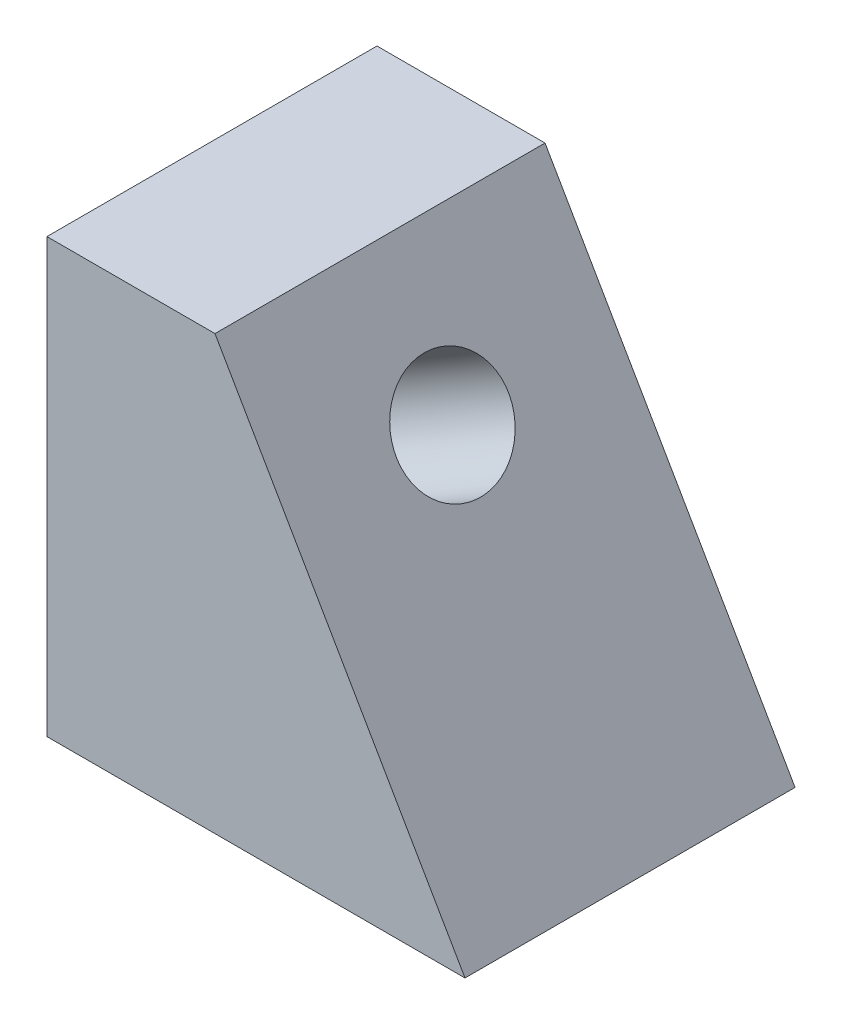
SolidWorks part; units mm, degrees
ref_plane "Front Plane" through (0, 0, 0) normal (0, 0, 1) x (1, 0, 0)
ref_plane "Top Plane" through (0, 0, 0) normal (0, 1, 0) x (1, 0, 0)
ref_plane "Right Plane" through (0, 0, 0) normal (1, 0, 0) x (0, 0, -1)
sketch "Sketch1" plane through (0, 0, 0) normal (0, 0, 1) x (1, 0, 0)
  line L1 (0, 0) -> (63.3351, 0)
  line L2 (0, 0) -> (0, 65.6066)
  line L3 (0, 65.6066) -> (63.3351, 65.6066)
  line L4 (63.3351, 0) -> (63.3351, 65.6066)
extrude "Boss-Extrude1" add sketch "Sketch1" along normal blind 50 contours L3 L4 L1 L2
sketch "Sketch2" plane through (0, 0, 50) normal (0, 0, 1) x (1, 0, 0)
  line L0 (63.3351, 0) -> (25.4571, 65.6066) construction
  line L1 (0, 65.6066) -> (63.3351, 65.6066) construction
  line L2 (0, 0) -> (63.3351, 0) construction
  line L3 (25.4571, 65.6066) -> (63.3351, 0)
  line L4 (63.3351, 0) -> (63.3351, 65.6066)
  line L5 (63.3351, 65.6066) -> (25.4571, 65.6066)
  line L6 (0, 30.3716) -> (45.8, 30.3716) construction
  line L7 (0, 0) -> (0, 65.6066) construction
  line L8 (0, 30.3716) -> (37.4018, 44.9178) construction
  dimension "D1" = 60
  dimension "D2" = 21.252
extrude "Cut-Extrude1" cut sketch "Sketch2" against normal up to surface (50 mm away) up to face at (31.6675, 32.8033, 0)
ref_plane "Plane1" through (47.5013, 27.4249, 0) normal (0.866, 0.5, 0) x (0, 0, -1)
sketch "Sketch3" plane through (47.5013, 27.4249, 0) normal (0.866, 0.5, 0) x (0, 0, -1)
  line L0 (-25, 44.0884) -> (-25, -31.6675) construction
  line L1 (0, 44.0884) -> (-50, 44.0884) construction
  line L2 (-50, -31.6675) -> (0, -31.6675) construction
  circle A0 centre (-25, 22.1434) radius 8.5
  dimension "D1" = 17
extrude "Cut-Extrude2" cut sketch "Sketch3" against normal up to surface (37.1578 mm away)
